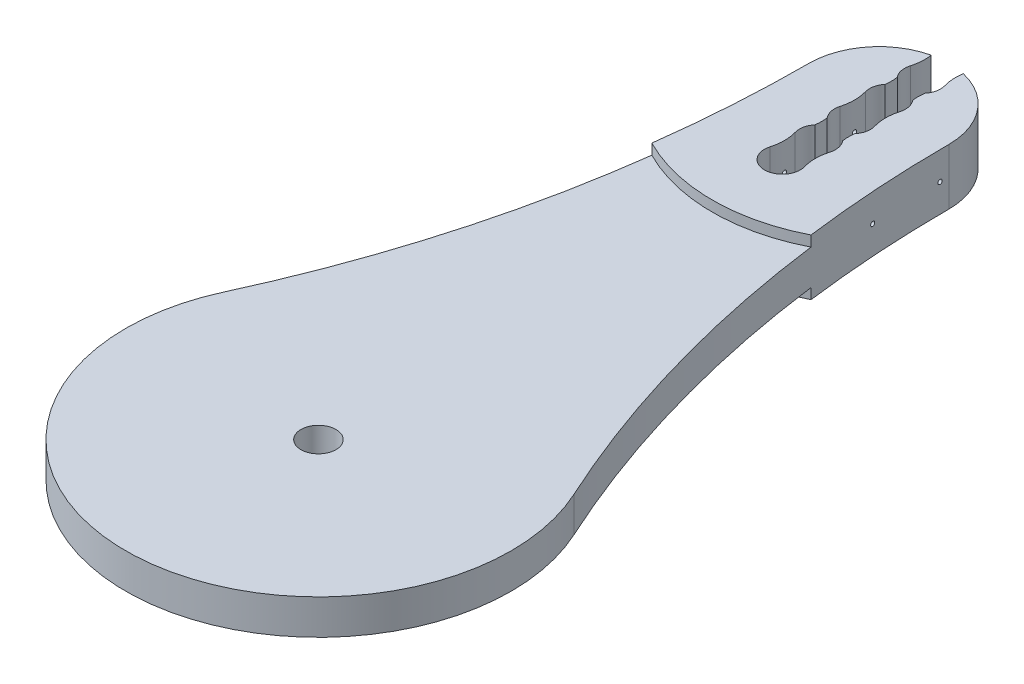
SolidWorks part; units mm, degrees
ref_plane "Front Plane" through (0, 0, 0) normal (0, 0, 1) x (1, 0, 0)
ref_plane "Top Plane" through (0, 0, 0) normal (0, 1, 0) x (1, 0, 0)
ref_plane "Right Plane" through (0, 0, 0) normal (1, 0, 0) x (0, 0, -1)
sketch "Sketch1" plane through (0, 0, 0) normal (0, 1, 0) x (1, 0, 0)
  line L0 (0, 101.6) -> (0, 0) construction
  line L1 (-34.0791, 7.6398) -> (-12.3924, 104.3781) construction
  line L2 (34.0791, 7.6398) -> (12.3924, 104.3781) construction
  line L3 (-12.7, 110.3431) -> (-12.7, 43.2615) construction
  line L4 (12.7, 110.3431) -> (12.7, 43.2615) construction
  circle A0 centre (0, 0) radius 34.925
  circle A1 centre (0, 101.6) radius 12.7
  circle A2 centre (0, 0) radius 3.175
  arc A3 (31.7352, 14.5819) -> (12.7, 101.6) centre (221.1161, 101.6) cw
  arc A4 (-31.7352, 14.5819) -> (-12.7, 101.6) centre (-221.1161, 101.6) ccw
  dimension "D1" = 69.85
  dimension "D2" = 25.4
  dimension "D4" = 6.35
  dimension "D3" = 101.6
extrude "Boss-Extrude1" add sketch "Sketch1" along normal mid plane 10.16
sketch "Sketch2" plane through (0, 0, 0) normal (0, 1, 0) x (1, 0, 0)
  line L0 (0, 0) -> (0, 116.7526) construction
  arc A0 (-2.2593, 105.0991) -> (-2.2593, 107.5102) centre (-10.6115, 106.3046) ccw construction
  arc A2 (2.2593, 107.5102) -> (2.2593, 105.0991) centre (10.6115, 106.3046) ccw construction
  arc A4 (-2.2593, 92.3991) -> (-2.2593, 94.8102) centre (-10.6115, 93.6046) ccw construction
  arc A6 (2.2593, 94.8102) -> (2.2593, 92.3991) centre (10.6115, 93.6046) ccw construction
  arc A8 (-2.8794, 97.6118) -> (-2.8794, 102.2975) centre (-10.9864, 99.9546) ccw construction
  arc A9 (-2.8794, 97.6118) -> (-2.2593, 94.8102) centre (0, 96.7796) ccw construction
  arc A10 (2.8794, 102.2975) -> (2.8794, 97.6118) centre (10.9864, 99.9546) ccw construction
  arc A11 (2.8794, 102.2975) -> (2.2593, 105.0991) centre (0, 103.1296) ccw construction
  arc A12 (-2.8794, 84.9118) -> (-2.8794, 89.5975) centre (-10.9864, 87.2546) ccw construction
  arc A13 (-2.8794, 84.9118) -> (2.8794, 84.9118) centre (0, 84.0796) ccw construction
  arc A14 (2.8794, 89.5975) -> (2.8794, 84.9118) centre (10.9864, 87.2546) ccw construction
  arc A15 (2.8794, 89.5975) -> (2.2593, 92.3991) centre (0, 90.4296) ccw construction
  arc A16 (-2.2593, 130.4991) -> (-2.5269, 134.1236) centre (-10.6115, 131.7046) ccw construction
  arc A17 (2.2593, 120.2102) -> (2.2593, 117.7991) centre (10.6115, 119.0046) ccw construction
  arc A18 (-2.8794, 123.0118) -> (-2.2593, 120.2102) centre (0, 122.1796) ccw construction
  arc A19 (2.5269, 134.1236) -> (2.2593, 130.4991) centre (10.6115, 131.7046) ccw construction
  arc A20 (-2.8794, 110.3118) -> (-2.8794, 114.9975) centre (-10.9864, 112.6546) ccw construction
  arc A21 (2.8794, 114.9975) -> (2.8794, 110.3118) centre (10.9864, 112.6546) ccw construction
  arc A23 (2.8794, 114.9975) -> (2.2593, 117.7991) centre (0, 115.8296) ccw construction
  arc A24 (-2.8794, 123.0118) -> (-2.8794, 127.6975) centre (-10.9864, 125.3546) ccw construction
  arc A25 (2.8794, 127.6975) -> (2.2593, 130.4991) centre (0, 128.5296) ccw construction
  arc A26 (-2.2593, 117.7991) -> (-2.2593, 120.2102) centre (-10.6115, 119.0046) ccw construction
  arc A29 (2.8794, 127.6975) -> (2.8794, 123.0118) centre (10.9864, 125.3546) ccw construction
  arc A30 (2.5269, 134.1236) -> (-2.5269, 134.1236) centre (0, 134.8796) ccw construction
  arc A31 (-2.8794, 110.3118) -> (-2.2593, 107.5102) centre (0, 109.4796) ccw construction
  arc A32 (-2.2593, 130.4991) -> (-2.8794, 127.6975) centre (0, 128.5296) ccw construction
  arc A33 (2.2593, 120.2102) -> (2.8794, 123.0118) centre (0, 122.1796) ccw construction
  arc A34 (-2.2593, 117.7991) -> (-2.8794, 114.9975) centre (0, 115.8296) ccw construction
  arc A35 (2.2593, 107.5102) -> (2.8794, 110.3118) centre (0, 109.4796) ccw construction
  arc A36 (-2.2593, 105.0991) -> (-2.8794, 102.2975) centre (0, 103.1296) ccw construction
  arc A37 (2.2593, 94.8102) -> (2.8794, 97.6118) centre (0, 96.7796) ccw construction
  arc A38 (-2.2593, 92.3991) -> (-2.8794, 89.5975) centre (0, 90.4296) ccw construction
  arc A39 (-2.5006, 105.2075) -> (-2.5006, 107.4018) centre (-10.6115, 106.3046) ccw
  arc A40 (-3.1234, 110.3823) -> (-2.5006, 107.4018) centre (0, 109.4796) ccw
  arc A41 (-3.1234, 110.3823) -> (-3.1234, 114.927) centre (-10.9864, 112.6546) ccw
  arc A42 (-2.5006, 117.9075) -> (-3.1234, 114.927) centre (0, 115.8296) ccw
  arc A43 (-2.5006, 117.9075) -> (-2.5006, 120.1018) centre (-10.6115, 119.0046) ccw
  arc A44 (-3.1234, 123.0823) -> (-2.5006, 120.1018) centre (0, 122.1796) ccw
  arc A45 (-3.1234, 123.0823) -> (-3.1234, 127.627) centre (-10.9864, 125.3546) ccw
  arc A46 (-2.5006, 130.6075) -> (-3.1234, 127.627) centre (0, 128.5296) ccw
  arc A47 (-2.5006, 130.6075) -> (-2.7702, 134.0508) centre (-10.6115, 131.7046) ccw
  arc A48 (2.7702, 134.0508) -> (-2.7702, 134.0508) centre (0, 134.8796) ccw
  arc A49 (2.7702, 134.0508) -> (2.5006, 130.6075) centre (10.6115, 131.7046) ccw
  arc A50 (3.1234, 127.627) -> (2.5006, 130.6075) centre (0, 128.5296) ccw
  arc A51 (3.1234, 127.627) -> (3.1234, 123.0823) centre (10.9864, 125.3546) ccw
  arc A52 (2.5006, 120.1018) -> (3.1234, 123.0823) centre (0, 122.1796) ccw
  arc A53 (2.5006, 120.1018) -> (2.5006, 117.9075) centre (10.6115, 119.0046) ccw
  arc A54 (3.1234, 114.927) -> (2.5006, 117.9075) centre (0, 115.8296) ccw
  arc A55 (3.1234, 114.927) -> (3.1234, 110.3823) centre (10.9864, 112.6546) ccw
  arc A56 (2.5006, 107.4018) -> (3.1234, 110.3823) centre (0, 109.4796) ccw
  arc A57 (2.5006, 107.4018) -> (2.5006, 105.2075) centre (10.6115, 106.3046) ccw
  arc A58 (3.1234, 102.227) -> (2.5006, 105.2075) centre (0, 103.1296) ccw
  arc A59 (3.1234, 102.227) -> (3.1234, 97.6823) centre (10.9864, 99.9546) ccw
  arc A60 (2.5006, 94.7018) -> (3.1234, 97.6823) centre (0, 96.7796) ccw
  arc A61 (2.5006, 94.7018) -> (2.5006, 92.5075) centre (10.6115, 93.6046) ccw
  arc A62 (3.1234, 89.527) -> (2.5006, 92.5075) centre (0, 90.4296) ccw
  arc A63 (3.1234, 89.527) -> (3.1234, 84.9823) centre (10.9864, 87.2546) ccw
  arc A64 (-3.1234, 84.9823) -> (3.1234, 84.9823) centre (0, 84.0796) ccw
  arc A65 (-3.1234, 84.9823) -> (-3.1234, 89.527) centre (-10.9864, 87.2546) ccw
  arc A66 (-2.5006, 92.5075) -> (-3.1234, 89.527) centre (0, 90.4296) ccw
  arc A67 (-2.5006, 92.5075) -> (-2.5006, 94.7018) centre (-10.6115, 93.6046) ccw
  arc A68 (-3.1234, 97.6823) -> (-2.5006, 94.7018) centre (0, 96.7796) ccw
  arc A69 (-3.1234, 97.6823) -> (-3.1234, 102.227) centre (-10.9864, 99.9546) ccw
  arc A70 (-2.5006, 105.2075) -> (-3.1234, 102.227) centre (0, 103.1296) ccw
extrude "Cut-Extrude2" cut sketch "Sketch2" against normal mid plane 11.43
sketch "Sketch4" plane through (0, 0, 0) normal (1, 0, 0) x (0, 0, -1)
  line L0 (102.227, 5.08) -> (97.6823, 5.08) construction
  line L1 (102.227, 5.08) -> (102.227, -5.08) construction
  line L2 (97.6823, -5.08) -> (102.227, -5.08) construction
  line L3 (97.6823, -5.08) -> (97.6823, 5.08) construction
  line L4 (89.527, 5.08) -> (84.9823, 5.08) construction
  line L5 (89.527, 5.08) -> (89.527, -5.08) construction
  line L6 (84.9823, -5.08) -> (89.527, -5.08) construction
  line L7 (84.9823, -5.08) -> (84.9823, 5.08) construction
  line L8 (102.227, 5.08) -> (97.6823, 5.08) construction
  line L9 (102.227, 5.08) -> (102.227, -5.08) construction
  line L10 (97.6823, -5.08) -> (102.227, -5.08) construction
  line L11 (97.6823, -5.08) -> (97.6823, 5.08) construction
  line L12 (89.527, 5.08) -> (84.9823, 5.08) construction
  line L13 (89.527, 5.08) -> (89.527, -5.08) construction
  line L14 (84.9823, -5.08) -> (89.527, -5.08) construction
  line L15 (84.9823, -5.08) -> (84.9823, 5.08) construction
  line L16 (97.6823, -5.08) -> (102.227, 5.08) construction
  line L17 (84.9823, -5.08) -> (89.527, 5.08) construction
  circle A0 centre (87.2546, 0) radius 0.3969
  circle A1 centre (99.9546, 0) radius 0.3969
  dimension "D1" = 0.7937
extrude "Cut-Extrude3" cut sketch "Sketch4" against normal through all both and the other way through all
sketch "Sketch11" plane through (0, 5.08, 0) normal (0, 1, 0) x (1, 0, 0)
  line L4 (-34.9084, 1.0752) -> (-31.7349, 104.1071)
  line L5 (34.9084, 1.0752) -> (31.7349, 104.1071)
  arc A0 (-31.7349, 104.1071) -> (31.7349, 104.1071) centre (0, 103.1296) ccw
  arc A2 (-31.7352, 14.5819) -> (31.7352, 14.5819) centre (0, 0) ccw construction
  arc A5 (-31.7352, 14.5819) -> (31.7352, 14.5819) centre (0, 0) ccw construction
  arc A6 (-34.9084, 1.0752) -> (34.9084, 1.0752) centre (0, 0) ccw
  point P2 (34.0903, 7.5899)
  point P5 (0, 0)
  point P6 (31.7352, 14.5819)
  point P7 (-34.0844, 7.6162)
  point P12 (34.0901, 7.6162)
  point P14 (0, 0)
  point P15 (30.6731, 94.9307)
  point P16 (0, 0)
  dimension "D1" = 31.75
extrude "Cut-Extrude8" cut sketch "Sketch11" against normal blind 1.905
mirror "Mirror1" about plane through (0, 0, 0) normal (0, 1, 0) of "Cut-Extrude8"
